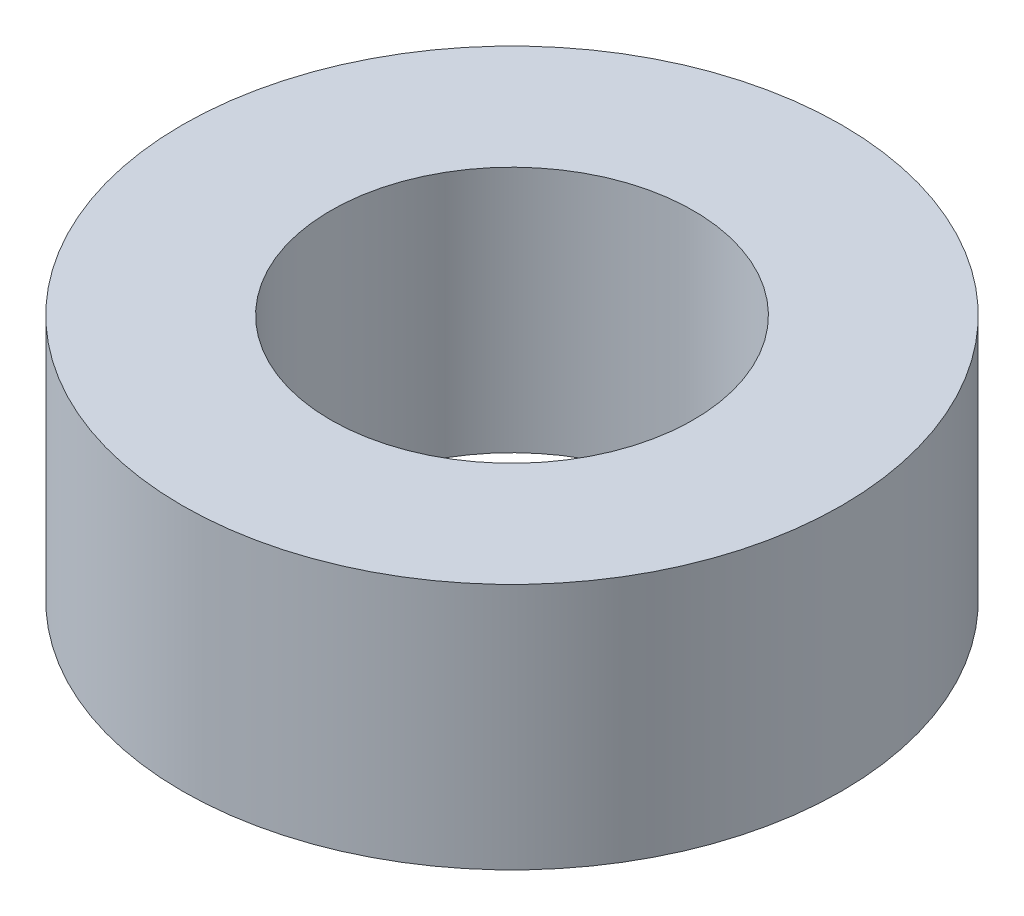
SolidWorks part; units mm, degrees
ref_plane "Front Plane" through (0, 0, 0) normal (0, 0, 1) x (1, 0, 0)
ref_plane "Top Plane" through (0, 0, 0) normal (0, 1, 0) x (1, 0, 0)
ref_plane "Right Plane" through (0, 0, 0) normal (1, 0, 0) x (0, 0, -1)
sketch "Sketch1" plane through (0, 0, 0) normal (0, 1, 0) x (1, 0, 0)
  circle A0 centre (0, 0) radius 4
  dimension "D1" = 8
extrude "Boss-Extrude1" add sketch "Sketch1" along normal blind 3
sketch "Sketch2" plane through (0, 3, 0) normal (0, 1, 0) x (1, 0, 0)
  circle A0 centre (0, 0) radius 4 construction
  circle A1 centre (0, 0) radius 4 construction
  circle A2 centre (0, 0) radius 2.2
  dimension "D1" = 4.4
extrude "Cut-Extrude1" cut sketch "Sketch2" against normal blind 3
